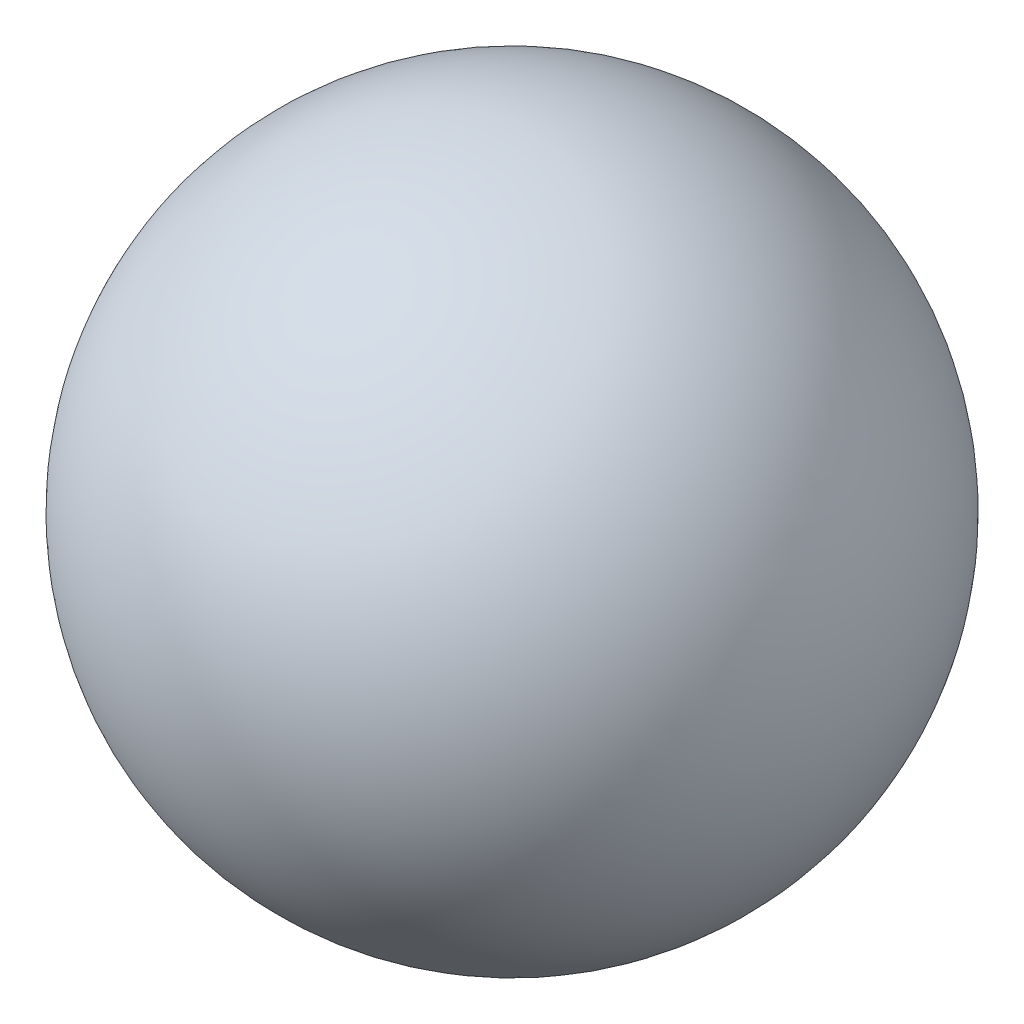
SolidWorks part; units mm, degrees
ref_plane "Plan1" through (0, 0, 0) normal (0, 0, 1) x (1, 0, 0)
ref_plane "Plan2" through (0, 0, 0) normal (0, 1, 0) x (1, 0, 0)
ref_plane "Plan3" through (0, 0, 0) normal (1, 0, 0) x (0, 0, -1)
ref_plane "Plan4" through (0, 0, 0) normal (0, 0, 1) x (1, 0, 0)
sketch "Esquisse2" plane through (0, 0, 0) normal (0, 0, 1) x (1, 0, 0)
  line L0 (2.6666, 0) -> (-2.6666, 0) construction
  line L2 (2.6666, 0) -> (-2.6666, 0)
  arc A0 (2.6666, 0) -> (-2.6666, 0) centre (0, 0) ccw
  dimension "D1" = 5.3333
revolve "Base-Révolution" add sketch "Esquisse2" angle 360 about L0
